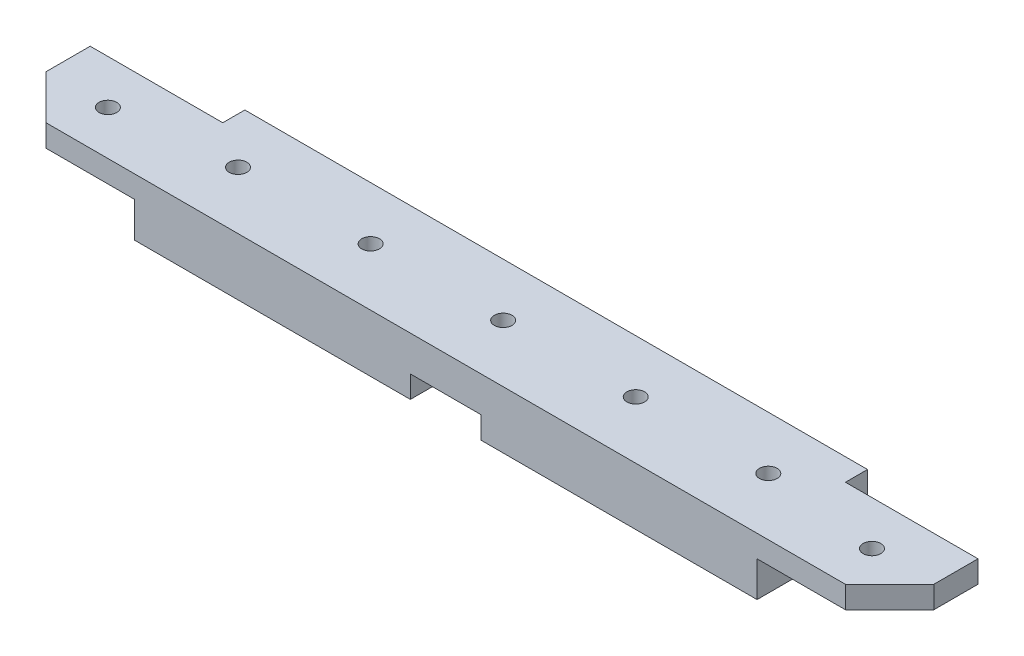
SolidWorks part; units mm, degrees
ref_plane "Front Plane" through (0, 0, 0) normal (0, 0, 1) x (1, 0, 0)
ref_plane "Top Plane" through (0, 0, 0) normal (0, 1, 0) x (1, 0, 0)
ref_plane "Right Plane" through (0, 0, 0) normal (1, 0, 0) x (0, 0, -1)
sketch "Sketch1" plane through (0, 0, 0) normal (0, 1, 0) x (1, 0, 0)
  line L0 (170.92, 20) -> (200.92, 20)
  line L1 (0, 0) -> (200.92, 0)
  line L2 (0, 0) -> (0, 20)
  line L3 (0, 20) -> (30, 20)
  line L4 (200.92, 0) -> (200.92, 20)
  line L6 (30, 20) -> (30, 25)
  line L7 (30, 25) -> (170.92, 25)
  line L8 (170.92, 20) -> (170.92, 25)
  dimension "D1" = 30
  dimension "D2" = 30
  dimension "D3" = 5
  dimension "D4" = 140.92
  dimension "D5" = 20
extrude "Boss-Extrude1" add sketch "Sketch1" along normal blind 5
sketch "Sketch2" plane through (0, 5, 0) normal (0, 1, 0) x (1, 0, 0)
  line L0 (-1000, 10) -> (49000, 10) construction
  line L1 (0, 20) -> (0, 0) construction
  line L3 (30, 25) -> (30, 20) construction
  line L4 (170.92, 20) -> (170.92, 25) construction
  circle A0 centre (14, 10) radius 2
  circle A1 centre (186.92, 10) radius 2
  point P5 (0, 10)
  dimension "D1" = 4
  dimension "D2" = 16
  dimension "D3" = 16
extrude "Cut-Extrude1" cut sketch "Sketch2" against normal through all
sketch "Sketch3" plane through (0, 0, 0) normal (0, 1, 0) x (1, 0, 0)
  line L0 (0, 0) -> (200.92, 0) construction
  line L1 (30, 25) -> (170.92, 25)
  line L2 (30, 25) -> (30, 0)
  line L3 (30, 0) -> (170.92, 0)
  line L4 (170.92, 25) -> (170.92, 0)
extrude "Boss-Extrude2" add sketch "Sketch3" against normal blind 8
sketch "Sketch4" plane through (0, 5, 0) normal (0, 1, 0) x (1, 0, 0)
  line L0 (100.46, -975) -> (100.46, 49025) construction
  line L1 (170.92, 25) -> (30, 25) construction
  circle A0 centre (70.46, 13) radius 2
  circle A1 centre (40.46, 13) radius 2
  circle A2 centre (160.46, 13) radius 2
  circle A3 centre (130.46, 13) radius 2
  point P5 (100.46, 25)
  dimension "D1" = 4
  dimension "D2" = 30
  dimension "D3" = 30
  dimension "D4" = 12
extrude "Cut-Extrude2" cut sketch "Sketch4" against normal through all
sketch "Sketch5" plane through (0, -8, 0) normal (0, -1, 0) x (1, 0, 0)
  circle A19 centre (40.46, -13) radius 4
  circle A21 centre (130.46, -13) radius 4
  circle A22 centre (160.46, -13) radius 4
  circle A23 centre (70.46, -13) radius 4
  dimension "D1" = 8
extrude "Cut-Extrude3" cut sketch "Sketch5" against normal blind 5
chamfer "Chamfer1" distance 10 angle 45 2 edges at (200.92, 2.5, 0) (0, 2.5, 0)
sketch "Sketch6" plane through (0, -8, 0) normal (0, -1, 0) x (1, 0, 0)
  line L0 (92.46, 0) -> (108.46, 0)
  line L1 (96.46, -17) -> (104.46, -17)
  line L2 (104.46, -17) -> (108.46, -10.0718)
  line L6 (92.46, -10.0718) -> (96.46, -17)
  line L7 (170.92, -25) -> (30, -25) construction
  line L8 (30, 0) -> (170.92, 0) construction
  line L9 (92.46, -10.0718) -> (92.46, 0)
  line L11 (108.46, -10.0718) -> (108.46, 0)
  line L14 (104.46, -3.1436) -> (96.46, -3.1436) [skipped]
  line L15 (96.46, -3.1436) -> (92.46, -10.0718) construction
  line L16 (108.46, -10.0718) -> (104.46, -3.1436) construction
  circle A0 centre (100.46, -10.0718) radius 6.9282 construction
  point P13 (100.46, 0)
  dimension "D1" = 8
  dimension "D2" = 8
  dimension "D3" = 16
extrude "Cut-Extrude4" cut sketch "Sketch6" against normal blind 5
sketch "Sketch8" plane through (0, -3, 0) normal (0, -1, 0) x (1, 0, 0)
  line L4 (108.46, 0) -> (92.46, 0) construction
  line L5 (170.92, -25) -> (30, -25) construction
  circle A0 centre (100.46, -13) radius 2
  point P4 (100.46, 0)
  dimension "D1" = 4
  dimension "D2" = 12
extrude "Cut-Extrude5" cut sketch "Sketch8" against normal through all
